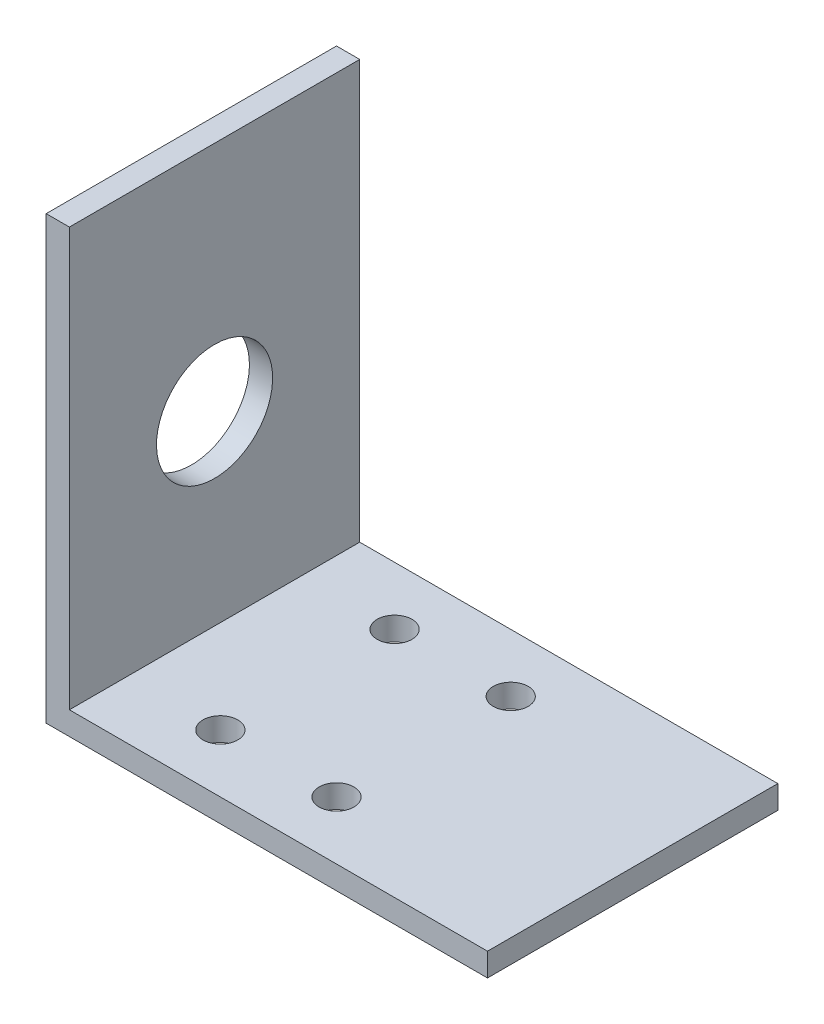
SolidWorks part; units mm, degrees
ref_plane "前视基准面" through (0, 0, 0) normal (0, 0, 1) x (1, 0, 0)
ref_plane "上视基准面" through (0, 0, 0) normal (0, 1, 0) x (1, 0, 0)
ref_plane "右视基准面" through (0, 0, 0) normal (1, 0, 0) x (0, 0, -1)
sketch "草图1" plane through (0, 0, 0) normal (0, 0, 1) x (1, 0, 0)
  line L0 (-11.5278, 18.6976) -> (-11.5278, -19.3024)
  line L1 (-11.5278, -19.3024) -> (26.4722, -19.3024)
  line L2 (26.4722, -19.3024) -> (26.4722, -17.3024)
  line L3 (26.4722, -17.3024) -> (-9.5278, -17.3024)
  line L4 (-9.5278, -17.3024) -> (-9.5278, 18.6976)
  line L5 (-9.5278, 18.6976) -> (-11.5278, 18.6976)
  dimension "D1" = 38
  dimension "D2" = 38
  dimension "D3" = 2
  dimension "D4" = 2
extrude "凸台-拉伸1" add sketch "草图1" along normal blind 25
sketch "草图2" plane through (0, -17.3024, 0) normal (0, 1, 0) x (1, 0, 0)
  line L0 (26.4722, 0) -> (-9.5278, 0) construction
  line L1 (-11.5278, -25) -> (-11.5278, 0) construction
  circle A0 centre (-1.5278, -5) radius 1.5
  circle A1 centre (8.4722, -5) radius 1.5
  circle A2 centre (8.4722, -20) radius 1.5
  circle A3 centre (-1.5278, -20) radius 1.5
  dimension "D1" = 15
  dimension "D2" = 15
  dimension "D3" = 10
  dimension "D4" = 10
  dimension "D5" = 5
  dimension "D6" = 5
  dimension "D7" = 3
  dimension "D8" = 3
  dimension "D9" = 3
  dimension "D10" = 3
  dimension "D11" = 10
  dimension "D12" = 10
extrude "切除-拉伸1" cut sketch "草图2" against normal through all
sketch "草图3" plane through (-9.5278, 0, 0) normal (1, 0, 0) x (0, 0, -1)
  line L0 (-25, -17.3024) -> (-25, 18.6976) construction
  line L1 (-25, -19.3024) -> (0, -19.3024) construction
  circle A0 centre (-12.5, -1.3024) radius 5
  dimension "D1" = 12.5
  dimension "D2" = 18
  dimension "D3" = 10
extrude "切除-拉伸2" cut sketch "草图3" against normal through all
